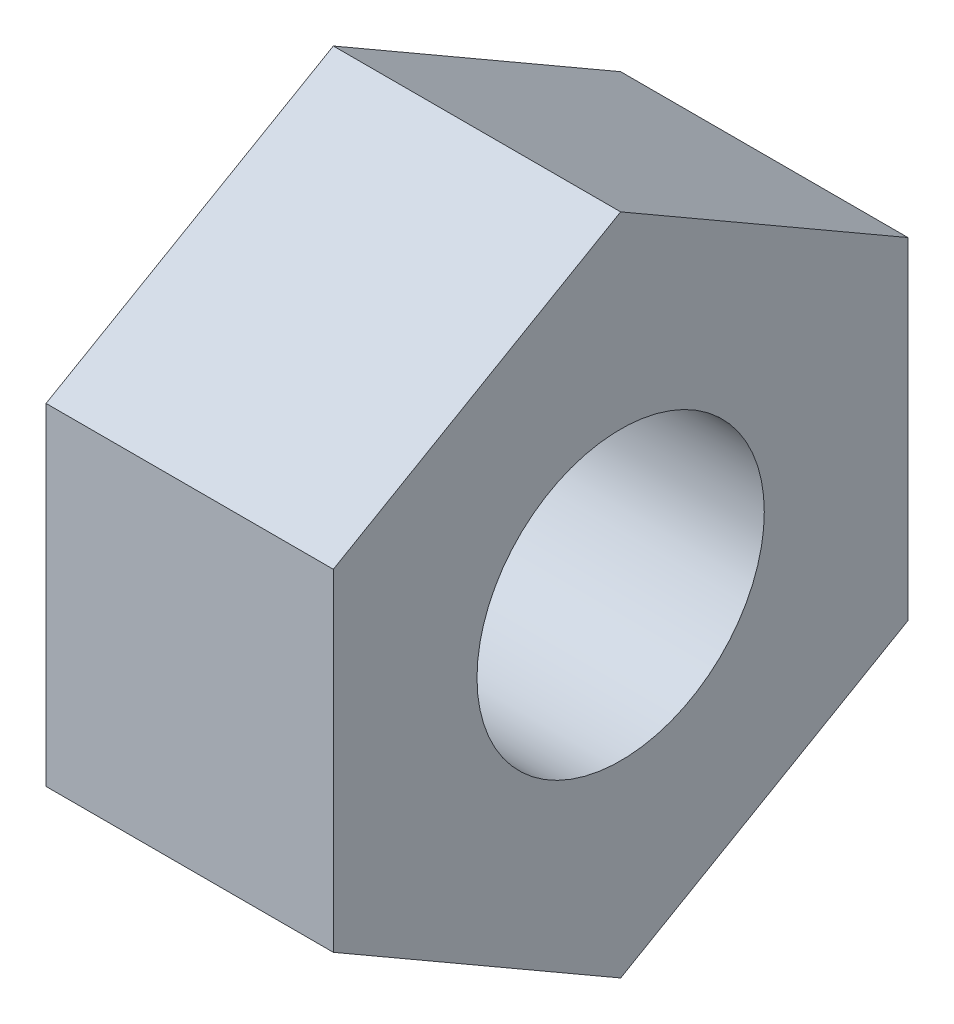
SolidWorks part; units mm, degrees
ref_plane "前视基准面" through (0, 0, 0) normal (0, 0, 1) x (1, 0, 0)
ref_plane "上视基准面" through (0, 0, 0) normal (0, 1, 0) x (1, 0, 0)
ref_plane "右视基准面" through (0, 0, 0) normal (1, 0, 0) x (0, 0, -1)
sketch "草图2" plane through (0, 0, 0) normal (1, 0, 0) x (0, 0, -1)
  line L1 (0, 2.3094) -> (-2, 1.1547)
  line L2 (-2, 1.1547) -> (-2, -1.1547)
  line L3 (-2, -1.1547) -> (0, -2.3094)
  line L4 (0, -2.3094) -> (2, -1.1547)
  line L5 (2, -1.1547) -> (2, 1.1547)
  line L6 (2, 1.1547) -> (0, 2.3094)
  circle A0 centre (0, 0) radius 2 construction
  circle A1 centre (0, 0) radius 1
  dimension "D2" = 2
  dimension "D1" = 4
extrude "凸台-拉伸1" add sketch "草图2" along normal blind 2
